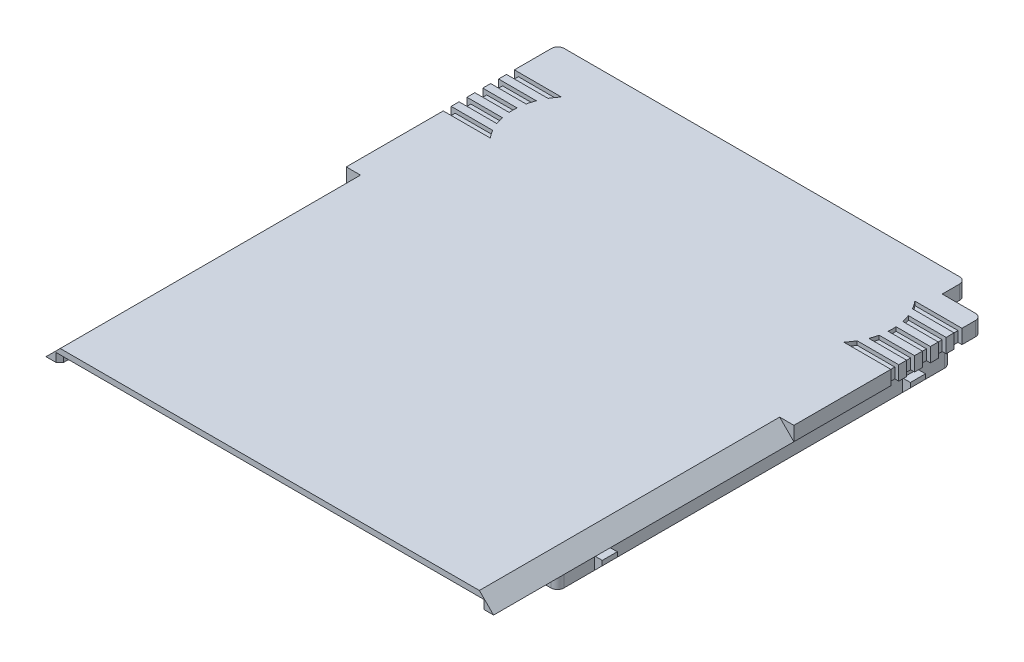
SolidWorks part; units mm, degrees
ref_plane "Front Plane" through (0, 0, 0) normal (0, 0, 1) x (1, 0, 0)
ref_plane "Top Plane" through (0, 0, 0) normal (0, 1, 0) x (1, 0, 0)
ref_plane "Right Plane" through (0, 0, 0) normal (1, 0, 0) x (0, 0, -1)
sketch "Sketch1" plane through (0, 0, 0) normal (0, 1, 0) x (1, 0, 0)
  line L0 (0, -32.385) -> (0, 32.385) construction
  line L1 (23.321, 32.385) -> (-28.321, 32.385)
  line L2 (28.321, 29.385) -> (28.321, -32.385)
  line L3 (28.321, -32.385) -> (-28.321, -32.385)
  line L4 (-28.321, 32.385) -> (-28.321, -32.385)
  line L5 (28.321, 32.385) -> (-28.321, -32.385) construction
  line L6 (28.321, -32.385) -> (-28.321, 32.385) construction
  line L9 (28.321, 29.385) -> (23.321, 29.385)
  line L10 (23.321, 32.385) -> (23.321, 29.385)
  point P0 (0, 0)
  dimension "D1" = 56.642
  dimension "D2" = 64.77
  dimension "D3" = 3
  dimension "D4" = 5
extrude "Boss-Extrude1" add sketch "Sketch1" along normal blind 5.2
sketch "Sketch12" plane through (0, 0, 0) normal (0, -1, 0) x (1, 0, 0)
  line L0 (0, 32.385) -> (0, -32.385) construction
  line L1 (28.321, 32.385) -> (28.321, -29.385) construction
  line L2 (23.321, -32.385) -> (-28.321, -32.385) construction
  line L7 (-25, -28.985) -> (19.921, -28.985)
  line L8 (19.921, -28.985) -> (19.921, -26.015)
  line L9 (19.921, -26.015) -> (25, -26.015)
  line L10 (25, -26.015) -> (25, 20.985)
  line L18 (-26.4, 22.385) -> (-26.4, -30.385)
  line L19 (-26.4, -30.385) -> (21.321, -30.385)
  line L20 (21.321, -30.385) -> (21.321, -27.415)
  line L21 (21.321, -27.415) -> (26.4, -27.415)
  line L22 (26.4, -27.415) -> (26.4, 22.385)
  line L36 (-25, 20.985) -> (-25, -28.985)
  line L37 (-26.4, 22.385) -> (26.4, 22.385)
  line L39 (-25, 20.985) -> (25, 20.985)
  line L41 (-25, 28.985) -> (-25, -28.985) construction
  line L43 (25, -26.015) -> (25, 28.985) construction
  line L44 (26.4, 30.385) -> (-26.4, 30.385) construction
  line L45 (25, 28.985) -> (-25, 28.985) construction
  line L46 (-28.321, 32.385) -> (28.321, 32.385) construction
  line L47 (-26.4, 30.385) -> (-26.4, -30.385) construction
  line L48 (26.4, -27.415) -> (26.4, 30.385) construction
  point P20 (0, 22.385)
  dimension "D3" = 1.4
  dimension "D4" = 10
  dimension "D1" = 50
  dimension "D5" = 47
  dimension "D6" = 2
  dimension "D7" = 7
  dimension "D2" = 1.4
extrude "Cut-Extrude9" cut sketch "Sketch12" against normal blind 3.4
sketch "Sketch13" plane through (0, 3.4, 0) normal (0, -1, 0) x (1, 0, 0)
  line L0 (28.321, 32.385) -> (-28.321, 32.385) construction
  line L1 (-26.575, 32.385) -> (26.575, 32.385)
  line L2 (-26.575, 32.385) -> (-26.575, 22.385)
  line L3 (-26.575, 22.385) -> (26.575, 22.385)
  line L4 (26.575, 32.385) -> (26.575, 22.385)
  line L5 (-26.4, 22.385) -> (26.4, 22.385) construction
  point P9 (0, 32.385)
  point P10 (0, 32.385)
  dimension "D1" = 53.15
extrude "Cut-Extrude10" cut sketch "Sketch13" against normal blind 0.6
sketch "Sketch14" plane through (0, 0, -30.385) normal (0, 0, -1) x (-1, 0, 0)
  line L0 (26.4, 1.6) -> (27.4, 1.6)
  line L1 (26.4, 3.4) -> (26.4, 0) construction
  line L2 (27.4, 1.6) -> (27.4, 1)
  line L3 (27.4, 1) -> (26.4, 0)
  line L4 (26.4, 0) -> (-21.321, 0) construction
  line L5 (26.4, 1.6) -> (26.4, 0)
  dimension "D1" = 1
  dimension "D2" = 45
  dimension "D3" = 0.6
extrude "Boss-Extrude4" add sketch "Sketch14" against normal blind 1.9 from offset 7.2 separate body offset against normal yes
pattern_linear "LPattern3" count 2 spacing 39 along (0, 0, 1) of "Boss-Extrude4"
mirror "Mirror4" about plane through (0, 0, 0) normal (1, 0, 0) of "LPattern3", "Boss-Extrude4"
sketch "Sketch15" plane through (0, 3.4, 0) normal (0, -1, 0) x (1, 0, 0)
  line L0 (0, 32.2026) -> (0, -32.385) construction
  line L1 (-28.321, -32.385) -> (23.321, -32.385) construction
  line L3 (26.575, 32.385) -> (-26.575, 32.385) construction
  line L4 (-25, 20.985) -> (25, 20.985) construction
  circle A0 centre (0, 15.535) radius 2
  circle A1 centre (0, 15.535) radius 0.75
  dimension "D1" = 4
  dimension "D2" = 1.5
  dimension "D3" = 3.45
  dimension "D4" = 16.85
extrude "Boss-Extrude5" add sketch "Sketch15" along normal blind 2.4
sketch "Sketch3" plane through (0, 0, 0) normal (0, -1, 0) x (1, 0, 0)
  line L1 (-27.821, -25.885) -> (-28.321, -25.885)
  line L2 (-27.821, -25.885) -> (-27.821, -26.885)
  line L3 (-27.821, -26.885) -> (-28.321, -26.885)
  line L4 (-28.321, -25.885) -> (-28.321, -26.885)
  line L7 (-28.321, -32.385) -> (-28.321, 32.385) construction
  line L8 (23.321, -32.385) -> (-28.321, -32.385) construction
  line L9 (0, 32.385) -> (0, -32.385) construction
  line L10 (0, 32.385) -> (0, -32.385) construction
  line L11 (28.321, -25.885) -> (28.321, -26.885)
  line L12 (27.821, -26.885) -> (28.321, -26.885)
  line L13 (27.821, -25.885) -> (27.821, -26.885)
  line L14 (27.821, -25.885) -> (28.321, -25.885)
  dimension "D1" = 0.5
  dimension "D2" = 1
  dimension "D3" = 5.5
extrude "Cut-Extrude2" cut sketch "Sketch3" against normal blind 5.6
pattern_linear "LPattern1" count 5 spacing 2 along (0, 0, 1) of "Cut-Extrude2"
sketch "Sketch20" plane through (0, 0, 32.385) normal (0, 0, 1) x (1, 0, 0)
  line L0 (-26.521, 5.2) -> (-28.321, 3.4)
  line L1 (-28.321, 5.2) -> (28.321, 5.2) construction
  line L2 (-28.321, 5.2) -> (-28.321, 3.4) construction
  line L3 (-28.321, 3.4) -> (-28.321, 5.2)
  line L4 (-28.321, 5.2) -> (-26.521, 5.2)
  dimension "D1" = 45
extrude "Cut-Extrude15" cut sketch "Sketch20" against normal blind 38
mirror "Mirror6" about plane through (0, 0, 0) normal (1, 0, 0) of "Cut-Extrude15"
sketch "Sketch21" plane through (0, 5.2, 0) normal (0, 1, 0) x (1, 0, 0)
  line L0 (23.321, 32.385) -> (-28.321, 32.385) construction
  line L104 (-27.821, 17.885) -> (-28.321, 17.885) construction
  line L105 (-28.321, 18.885) -> (-27.821, 18.885) construction
  line L108 (-17, 15.385) -> (17, 15.385) construction
  line L109 (17, 29.385) -> (-17, 29.385) construction
  line L110 (-27.821, 19.885) -> (-28.321, 19.885) construction
  line L111 (-28.321, 20.885) -> (-27.821, 20.885) construction
  line L112 (-27.821, 21.885) -> (-28.321, 21.885) construction
  line L113 (-28.321, 22.885) -> (-27.821, 22.885) construction
  line L114 (-27.821, 23.885) -> (-28.321, 23.885) construction
  line L115 (-28.321, 24.885) -> (-27.821, 24.885) construction
  line L116 (-27.821, 25.885) -> (-28.321, 25.885) construction
  line L117 (-28.321, 26.885) -> (-27.821, 26.885) construction
  line L118 (-22.3619, 17.885) -> (-28.321, 17.885)
  line L119 (-28.321, 18.885) -> (-23.0622, 18.885)
  line L120 (-23.5383, 19.885) -> (-28.321, 19.885)
  line L121 (-28.321, 20.885) -> (-23.8374, 20.885)
  line L122 (-23.9821, 21.885) -> (-28.321, 21.885)
  line L148 (-28.321, 22.885) -> (-23.9821, 22.885)
  line L149 (-23.8374, 23.885) -> (-28.321, 23.885)
  line L150 (-28.321, 24.885) -> (-23.5383, 24.885)
  line L151 (-23.0622, 25.885) -> (-28.321, 25.885)
  line L152 (-28.321, 26.885) -> (-22.3619, 26.885)
  line L153 (-28.321, 26.885) -> (-28.321, 25.885)
  line L154 (-28.321, 24.885) -> (-28.321, 23.885)
  line L155 (-28.321, 22.885) -> (-28.321, 21.885)
  line L156 (-28.321, 20.885) -> (-28.321, 19.885)
  line L157 (-28.321, 18.885) -> (-28.321, 17.885)
  arc A0 (-22.3619, 26.885) -> (-23.0622, 25.885) centre (-17, 22.385) ccw
  arc A1 (-23.5383, 24.885) -> (-23.8374, 23.885) centre (-17, 22.385) ccw
  arc A2 (-23.9821, 22.885) -> (-23.9821, 21.885) centre (-17, 22.385) ccw
  arc A3 (-23.8374, 20.885) -> (-23.5383, 19.885) centre (-17, 22.385) ccw
  arc A4 (-23.0622, 18.885) -> (-22.3619, 17.885) centre (-17, 22.385) ccw
  arc A10 (17, 15.385) -> (17, 29.385) centre (17, 22.385) ccw construction
  arc A11 (-17, 29.385) -> (-17, 15.385) centre (-17, 22.385) ccw construction
  point P24 (0, 29.385)
  dimension "D2" = 7
  dimension "D4" = 48
  dimension "D1" = 14
  dimension "D3" = 3
extrude "Cut-Extrude16" cut sketch "Sketch21" against normal blind 0.5
mirror "Mirror7" about plane through (0, 0, 0) normal (1, 0, 0) of "Cut-Extrude16"
chamfer "Chamfer1" distance 0.5 angle 45 3 edges at (-26.575, 3.7, 32.385) (26.575, 3.7, 32.385) (0, 4, 32.385)
fillet "Fillet1" radius 0.8 9 edges at (-26.4, 1.7, 22.385) (26.4, 1.7, 22.385) (19.921, 1.7, -26.015) (21.321, 1.7, -30.385) (26.4, 1.7, -27.415) (28.321, 4.3, -29.385) (23.321, 4.3, -32.385) (-26.4, 1.7, -30.385) (-28.321, 4.3, -32.385)
fillet "Fillet2" [suppressed] radius 0.2
sketch "Sketch27" plane through (0, 4, 0) normal (0, -1, 0) x (1, 0, 0)
  line L0 (-26.575, 31.885) -> (26.575, 31.885) construction
  dimension "D1" = 53.15
sketch "Sketch28" plane through (21.321, 0, 0) normal (1, 0, 0) x (0, 0, -1)
  line L0 (30.385, 1.6) -> (31.385, 1.6)
  line L1 (30.385, 3.4) -> (30.385, 0) construction
  line L2 (31.385, 1.6) -> (31.385, 1)
  line L3 (31.385, 1) -> (30.385, 0)
  line L4 (30.385, 0) -> (30.385, 1.6)
  line L5 (29.585, 0) -> (30.385, 0) construction
  dimension "D1" = 45
  dimension "D2" = 0.6
  dimension "D3" = 1
extrude "Boss-Extrude6" add sketch "Sketch28" against normal blind 1.9 from offset 21 offset against normal yes
sketch "Sketch29" plane through (0, 3.4, 0) normal (0, -1, 0) x (1, 0, 0)
  circle A1 centre (0, 15.535) radius 0.75
  circle A2 centre (0, 15.535) radius 0.75
  dimension "D1" = 0
extrude "Cut-Extrude17" cut sketch "Sketch29" against normal blind 1
